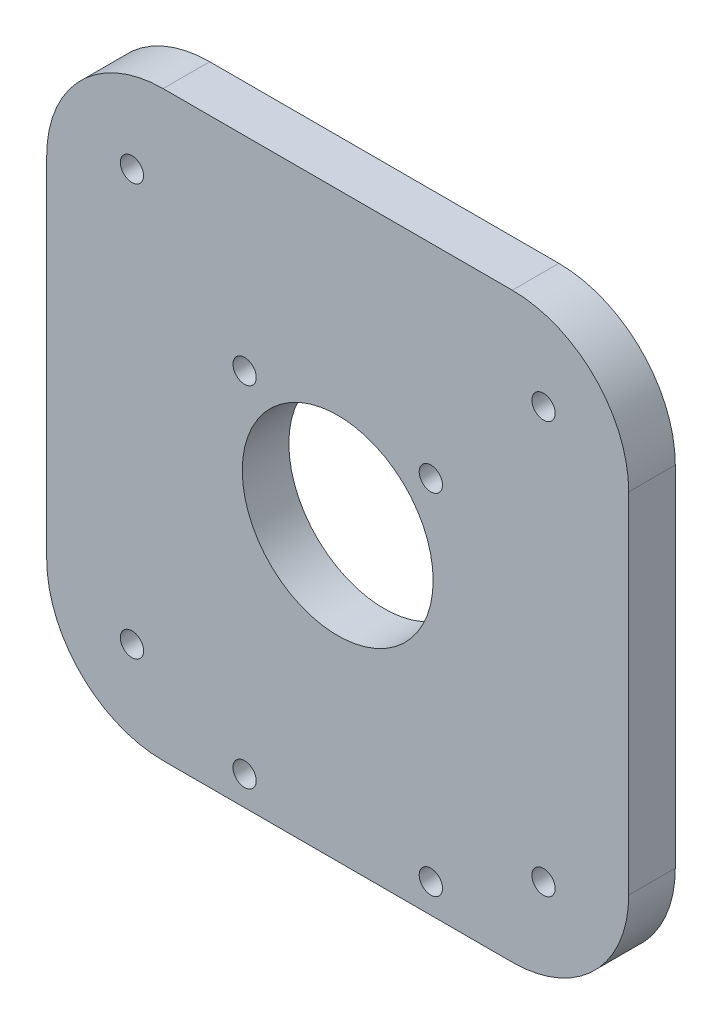
SolidWorks part; units mm, degrees
ref_plane "Front Plane" through (0, 0, 0) normal (0, 0, 1) x (1, 0, 0)
ref_plane "Top Plane" through (0, 0, 0) normal (0, 1, 0) x (1, 0, 0)
ref_plane "Right Plane" through (0, 0, 0) normal (1, 0, 0) x (0, 0, -1)
sketch "Sketch1" plane through (0, 0, 0) normal (0, 0, 1) x (1, 0, 0)
  line L1 (-25, -25) -> (25, -25)
  line L2 (-25, -25) -> (-25, 25)
  line L3 (-25, 25) -> (25, 25)
  line L4 (25, -25) -> (25, 25)
  line L5 (-25, -25) -> (25, 25) construction
  line L6 (-25, 25) -> (25, -25) construction
  point P0 (0, 0)
  dimension "D1" = 50
  dimension "D2" = 50
extrude "Boss-Extrude1" add sketch "Sketch1" along normal blind 4
sketch "Sketch2" plane through (0, 0, 4) normal (0, 0, 1) x (1, 0, 0)
  line L2 (-8, 7.5) -> (8, 7.5) construction
  line L3 (-8, 7.5) -> (-8, -22.5) construction
  line L4 (-8, -22.5) -> (8, -22.5) construction
  line L5 (8, 7.5) -> (8, -22.5) construction
  circle A0 centre (0, 0) radius 8.2
  circle A1 centre (-8, 7.5) radius 1
  circle A2 centre (8, 7.5) radius 1
  circle A3 centre (-8, -22.5) radius 1
  circle A4 centre (8, -22.5) radius 1
  point P7 (0, 7.5)
  dimension "D1" = 16.4
  dimension "D5" = 2
  dimension "D6" = 2
  dimension "D7" = 2
  dimension "D8" = 2
  dimension "D2" = 16
  dimension "D3" = 30
  dimension "D4" = 7.5
extrude "Cut-Extrude1" cut sketch "Sketch2" against normal blind 10
sketch "Sketch3" plane through (0, 0, 4) normal (0, 0, 1) x (1, 0, 0)
  line L0 (-25, 25) -> (25, -25) construction
  line L1 (25, 25) -> (-25, -25) construction
  circle A0 centre (-17.6777, 17.6777) radius 1
  circle A1 centre (17.6777, 17.6777) radius 1
  circle A2 centre (17.6777, -17.6777) radius 1
  circle A3 centre (-17.6777, -17.6777) radius 1
  point P10 (-15.0942, 19.929)
  point P20 (0, 0)
  dimension "D1" = 2
  dimension "D2" = 25
  dimension "D3" = 4
extrude "Cut-Extrude2" cut sketch "Sketch3" against normal up to vertex (4 mm away) up to point (0, 0, 0)
fillet "Fillet1" radius 10 4 edges at (-25, -25, 2) (25, -25, 2) (25, 25, 2) (-25, 25, 2)
